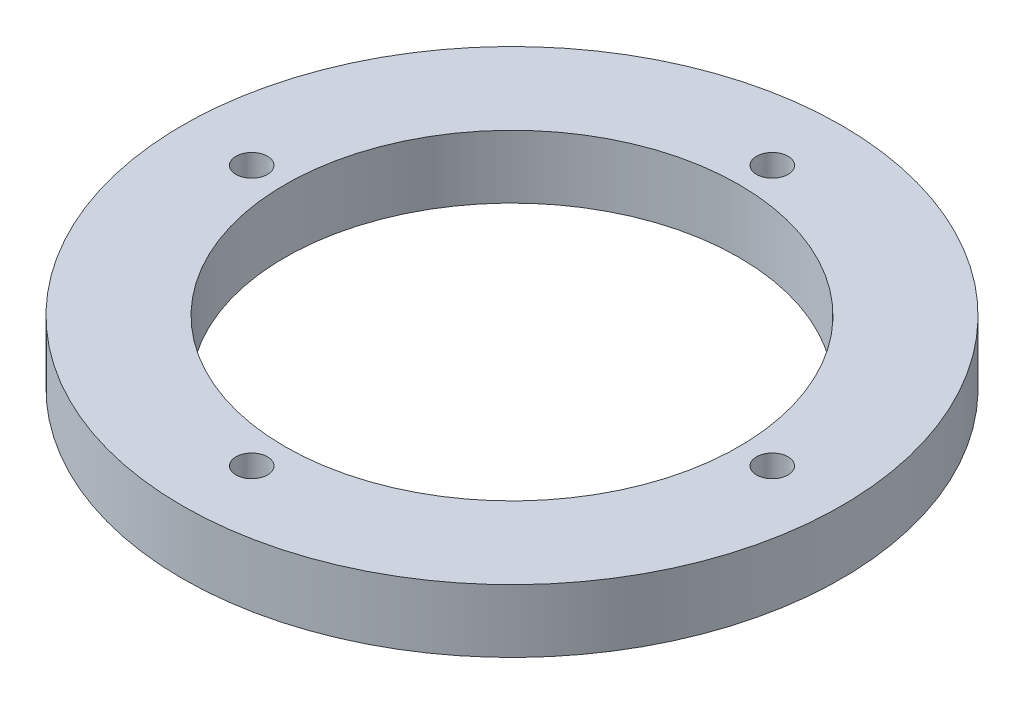
SolidWorks part; units mm, degrees
ref_plane "Front Plane" through (0, 0, 0) normal (0, 0, 1) x (1, 0, 0)
ref_plane "Top Plane" through (0, 0, 0) normal (0, 1, 0) x (1, 0, 0)
ref_plane "Right Plane" through (0, 0, 0) normal (1, 0, 0) x (0, 0, -1)
sketch "Sketch1" plane through (0, 0, 0) normal (0, 1, 0) x (1, 0, 0)
  circle A0 centre (0, 0) radius 20.64 construction
  circle A1 centre (0, 20.64) radius 1.25
  circle A2 centre (-20.64, 0) radius 1.25
  circle A3 centre (0, -20.64) radius 1.25
  circle A4 centre (20.64, 0) radius 1.25
  circle A5 centre (0, 0) radius 18
  circle A6 centre (0, 0) radius 26.1324
  dimension "D1" = 41.28
  dimension "D2" = 2.5
extrude "Boss-Extrude1" add sketch "Sketch1" along normal blind 5
